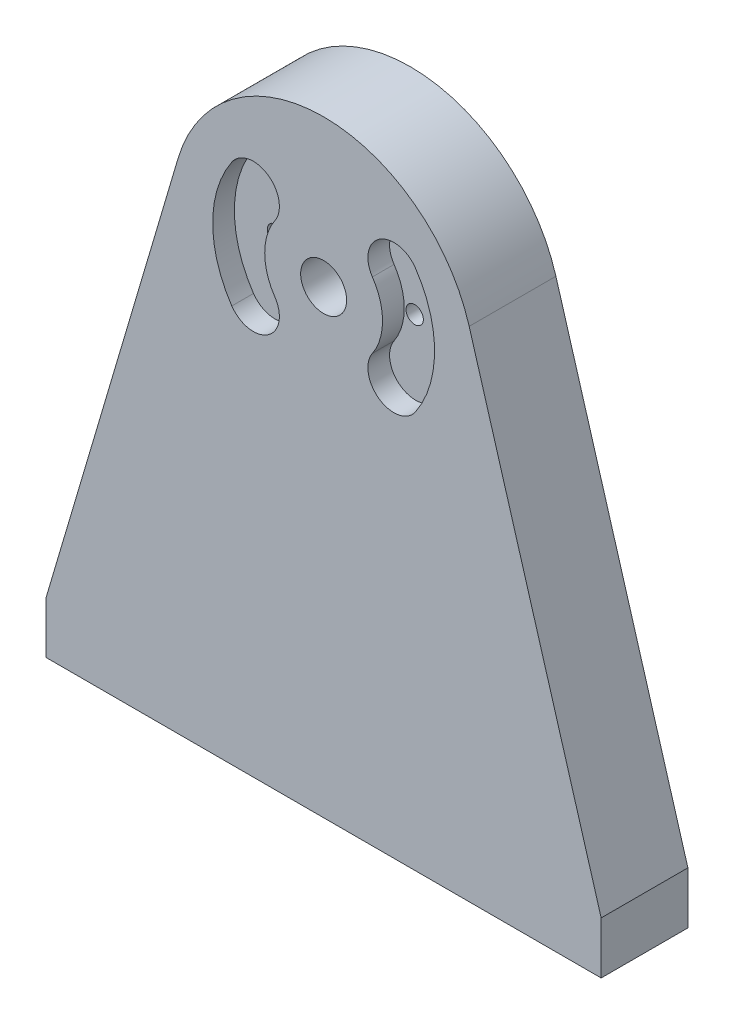
SolidWorks part; units mm, degrees
ref_plane "정면" through (0, 0, 0) normal (0, 0, 1) x (1, 0, 0)
ref_plane "윗면" through (0, 0, 0) normal (0, 1, 0) x (1, 0, 0)
ref_plane "우측면" through (0, 0, 0) normal (1, 0, 0) x (0, 0, -1)
sketch "스케치1" plane through (0, 0, 0) normal (0, 0, 1) x (1, 0, 0)
  line L0 (0, 70) -> (0, 0) construction
  line L1 (-32, 0) -> (32, 0)
  line L2 (32, 0) -> (32, 6)
  line L3 (32, 6) -> (16.7816, 57.4626)
  line L4 (-32, 0) -> (-32, 6)
  line L5 (-32, 6) -> (-16.7816, 57.4626)
  arc A0 (16.7816, 57.4626) -> (-16.7816, 57.4626) centre (0, 52.5) ccw
  dimension "D4" = 35
  dimension "D2" = 32
  dimension "D3" = 6
extrude "보스-돌출1" add sketch "스케치1" along normal mid plane 10
hole_wizard "M5 여유 구멍1" positions "스케치2" profile "스케치3" hole size "M5" standard "KS" end condition through all
sketch "스케치2" plane through (0, 0, 5) normal (0, 0, 1) x (1, 0, 0)
  point P0 (0, 53)
  dimension "D1" = 53
sketch "스케치3" plane through (0, 53, 5) normal (1, 0, 0) x (0, -1, 0)
  line L0 (0, 0) -> (0, 10)
  line L1 (0, 10) -> (2.65, 10)
  line L2 (2.65, 10) -> (2.65, 0)
  line L5 (2.65, 0) -> (0, 0)
  line L11 (0, -6.35) -> (0, 107.95) construction
  dimension "관통 구멍 지름" = 5.3
  dimension "관통 구멍 깊이" = 10
sketch "스케치4" plane through (0, 0, 5) normal (0, 0, 1) x (1, 0, 0)
  line L0 (-9.7936, 53) -> (0, 53) construction
  arc A0 (-8.1033, 58.5) -> (-8.1033, 47.5) centre (0, 53) ccw construction
  arc A1 (-10.5856, 60.1848) -> (-10.5856, 45.8152) centre (0, 53) ccw
  arc A2 (-5.6211, 56.8152) -> (-5.6211, 49.1848) centre (0, 53) ccw
  arc A3 (-5.6211, 56.8152) -> (-10.5856, 60.1848) centre (-8.1033, 58.5) ccw
  arc A4 (-10.5856, 45.8152) -> (-5.6211, 49.1848) centre (-8.1033, 47.5) ccw
  point P4 (-9.7936, 53)
  dimension "D1" = 3
  dimension "D2" = 11
extrude "컷-돌출1" cut sketch "스케치4" against normal blind 2.5
hole_wizard "Ø2.0 (2) 지름 구멍1" positions "스케치5" profile "스케치6" hole size "Ø2.0" standard "KS"
sketch "스케치5" plane through (0, 0, 5) normal (0, 0, 1) x (1, 0, 0)
  line L0 (-8, 53) -> (0, 53) construction
  point P0 (-8, 53)
  dimension "D1" = 8
sketch "스케치6" plane through (-8, 53, 5) normal (1, 0, 0) x (0, -1, 0)
  line L0 (0, 0) -> (0, 5)
  line L1 (0, 5) -> (1, 5)
  line L2 (1, 5) -> (1, 0)
  line L5 (1, 0) -> (0, 0)
  line L10 (0, 5) -> (-1, 5) construction
  line L11 (0, -6.35) -> (0, 107.95) construction
  dimension "구멍 지름" = 2
  dimension "구멍 깊이" = 5
  dimension "드릴 각도" = 180
mirror "대칭 복사1" about plane through (0, 0, 0) normal (1, 0, 0) of "Ø2.0 (2) 지름 구멍1", "컷-돌출1"
hole_wizard "Ø2.0 (2) 지름 구멍2" positions "스케치7" profile "스케치8" hole size "Ø2.0" standard "KS"
sketch "스케치7" plane through (0, 0, 0) normal (0, -1, 0) x (-1, 0, 0)
  line L0 (0, 5) -> (0, -5) construction
  line L1 (32, 5) -> (-32, 5) construction
  line L2 (32, -5) -> (-32, -5) construction
  line L3 (-32, -5) -> (-32, 5) construction
  point P0 (-8, 0)
  point P2 (8, 0)
  dimension "D1" = 24
sketch "스케치8" plane through (8, 0, 0) normal (1, 0, 0) x (0, 0, -1)
  line L0 (0, 0) -> (0, 55)
  line L1 (0, 55) -> (1, 55)
  line L2 (1, 55) -> (1, 0)
  line L5 (1, 0) -> (0, 0)
  line L10 (0, 55) -> (-1, 55) construction
  line L11 (0, -6.35) -> (0, 107.95) construction
  dimension "구멍 지름" = 2
  dimension "구멍 깊이" = 55
  dimension "드릴 각도" = 180
hole_wizard "M5 여유 구멍2" positions "스케치9" profile "스케치10" hole size "M5" standard "KS"
sketch "스케치9" plane through (0, 0, 0) normal (0, -1, 0) x (-1, 0, 0)
  line L0 (0, 5) -> (0, -5) construction
  line L1 (32, 5) -> (-32, 5) construction
  line L2 (32, -5) -> (-32, -5) construction
  line L3 (-32, -5) -> (-32, 5) construction
  point P0 (-22, 0)
  point P2 (22, 0)
  dimension "D1" = 10
sketch "스케치10" plane through (22, 0, 0) normal (1, 0, 0) x (0, 0, -1)
  line L0 (0, 0) -> (0, 12.4)
  line L1 (0, 12.4) -> (2.65, 12.4)
  line L2 (2.65, 12.4) -> (2.65, 0)
  line L5 (2.65, 0) -> (0, 0)
  line L10 (0, 12.4) -> (-2.65, 12.4) construction
  line L11 (0, -6.35) -> (0, 107.95) construction
  dimension "구멍 지름" = 5.3
  dimension "구멍 깊이" = 12.4
  dimension "드릴 각도" = 180
